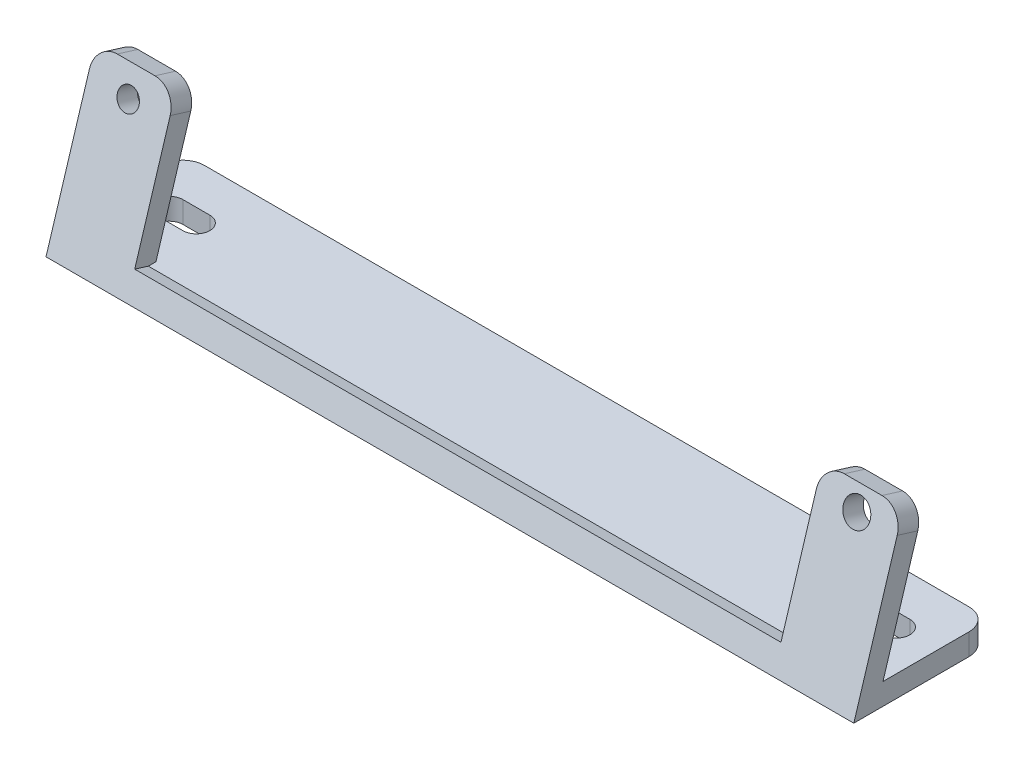
SolidWorks part; units mm, degrees
ref_plane "Front Plane" through (0, 0, 0) normal (0, 0, 1) x (1, 0, 0)
ref_plane "Top Plane" through (0, 0, 0) normal (0, 1, 0) x (1, 0, 0)
ref_plane "Right Plane" through (0, 0, 0) normal (1, 0, 0) x (0, 0, -1)
sketch "Sketch1" plane through (0, 0, 0) normal (0, 1, 0) x (1, 0, 0)
  line L0 (-67.5, 0) -> (-62.5, 0) construction
  line L1 (-75, 10) -> (75, 10)
  line L2 (-75, 10) -> (-75, -10)
  line L3 (-75, -10) -> (75, -10)
  line L4 (75, 10) -> (75, -10)
  line L5 (-75, 10) -> (75, -10) construction
  line L6 (-75, -10) -> (75, 10) construction
  line L7 (-67.5, 2.5) -> (-62.5, 2.5)
  line L8 (-67.5, -2.5) -> (-62.5, -2.5)
  line L9 (62.5, 0) -> (67.5, 0) construction
  line L10 (62.5, 2.5) -> (67.5, 2.5)
  line L11 (62.5, -2.5) -> (67.5, -2.5)
  arc A0 (-67.5, 2.5) -> (-67.5, -2.5) centre (-67.5, 0) ccw
  arc A1 (-62.5, -2.5) -> (-62.5, 2.5) centre (-62.5, 0) ccw
  arc A2 (62.5, 2.5) -> (62.5, -2.5) centre (62.5, 0) ccw
  arc A3 (67.5, -2.5) -> (67.5, 2.5) centre (67.5, 0) ccw
  point P0 (0, 0)
  point P8 (-65, 0)
  point P13 (65, 0)
  dimension "D3" = 2.5
  dimension "D4" = 2.5
  dimension "D1" = 150
  dimension "20" = 20
  dimension "D5" = 5
  dimension "D6" = 5
  dimension "D7" = 130
  dimension "D8" = 65
extrude "Boss-Extrude1" add sketch "Sketch1" along normal blind 4
sketch "Sketch3" plane through (75, 0, 0) normal (1, 0, 0) x (0, 0, -1)
  line L0 (-10, 0) -> (-15.4166, 0)
  line L1 (-15.4166, 0) -> (-6.1816, 30)
  line L2 (-6.1816, 30) -> (-2.3587, 28.8232)
  line L3 (-2.3587, 28.8232) -> (-10, 4)
  line L4 (-10, 4) -> (-10, 0)
  line L5 (-10, 4) -> (10, 4) construction
  dimension "D1" = 4
  dimension "D2" = 4
  dimension "D3" = 30
  dimension "D4" = 72.89
extrude "Boss-Extrude3" add sketch "Sketch3" against normal up to surface (150 mm away) up to face at (-75, 2, 0)
sketch "Sketch4" plane through (0, 4.3349, 14.0821) normal (0, 0.2942, 0.9557) x (1, 0, 0)
  line L0 (-75, 26.8536) -> (75, 26.8536) construction
  line L1 (-60, 26.8536) -> (60, 26.8536)
  line L2 (-60, 26.8536) -> (-60, 0.4643)
  line L3 (-60, 0.4643) -> (60, 0.4643)
  line L4 (60, 26.8536) -> (60, 0.4643)
  line L5 (-75, -4.5357) -> (-75, 26.8536) construction
  line L6 (75, 26.8536) -> (75, -4.5357) construction
  line L7 (-75, -4.5357) -> (75, -4.5357) construction
  circle A0 centre (-67.5, 21.8536) radius 2.005
  circle A1 centre (67.5, 22.8436) radius 2.5
  dimension "D4" = 4.01
  dimension "D8" = 5
  dimension "D9" = 7.5
  dimension "D1" = 15
  dimension "D2" = 15
  dimension "D3" = 5
  dimension "D5" = 7.5
  dimension "D6" = 5
  dimension "D7" = 4.01
extrude "Cut-Extrude1" cut sketch "Sketch4" against normal blind 10
fillet "Fillet1" radius 4 6 edges at (-75, 2, -10) (75, 2, -10) (60, 29.4116, 4.2701) (75, 29.4116, 4.2701) (-60, 29.4116, 4.2701) (-75, 29.4116, 4.2701)
sketch "Sketch5" plane through (75, 0, 0) normal (1, 0, 0) x (0, 0, -1)
  line L0 (6, 4) -> (6, 0)
  line L1 (6, 0) -> (-15.4166, 0)
  line L2 (-15.4166, 0) -> (-14.1852, 4)
  line L3 (-7.3584, 26.177) -> (-15.4166, 0) construction
  line L4 (-14.1852, 4) -> (6, 4)
extrude "Boss-Extrude4" add sketch "Sketch5" against normal up to surface (150 mm away) up to face at (-75, 9.8629, 4.0517)
sketch "Sketch7" plane through (0, 0, 0) normal (0, -1, 0) x (1, 0, 0)
  line L0 (-62.5, 0) -> (-67.5, 0) construction
  line L1 (-62.5, -2.5) -> (-67.5, -2.5)
  line L2 (-62.5, 2.5) -> (-67.5, 2.5)
  line L3 (62.5, 0) -> (67.5, 0) construction
  line L4 (62.5, 2.5) -> (67.5, 2.5)
  line L5 (62.5, -2.5) -> (67.5, -2.5)
  line L6 (-75, -6) -> (-75, 15.4166) construction
  arc A0 (-62.5, -2.5) -> (-62.5, 2.5) centre (-62.5, 0) ccw
  arc A1 (-67.5, 2.5) -> (-67.5, -2.5) centre (-67.5, 0) ccw
  arc A2 (62.5, 2.5) -> (62.5, -2.5) centre (62.5, 0) ccw
  arc A3 (67.5, -2.5) -> (67.5, 2.5) centre (67.5, 0) ccw
  point P3 (-65, 0)
  point P8 (65, 0)
  dimension "D1" = 2.5
  dimension "D3" = 2.5
  dimension "D2" = 7.5
  dimension "D4" = 130
  dimension "D5" = 65
  dimension "D6" = 5
  dimension "D7" = 5
extrude "Cut-Extrude4" cut sketch "Sketch7" against normal blind 10
